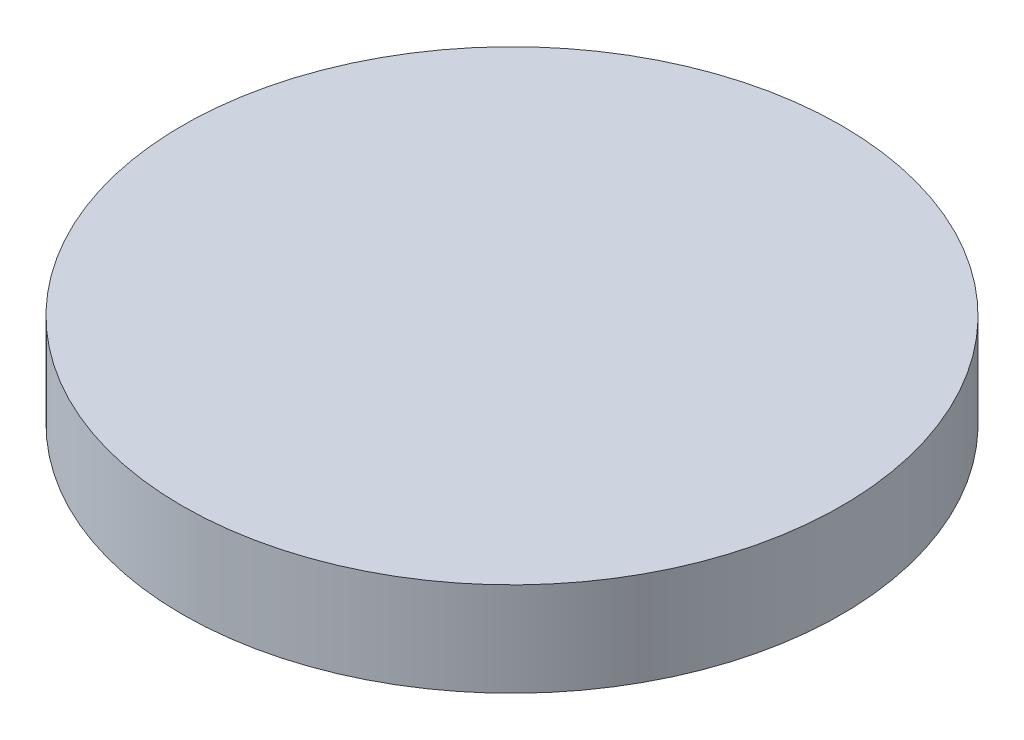
SolidWorks part; units mm, degrees
ref_plane "Front" through (0, 0, 0) normal (0, 0, 1) x (1, 0, 0)
ref_plane "Top" through (0, 0, 0) normal (0, 1, 0) x (1, 0, 0)
ref_plane "Right" through (0, 0, 0) normal (1, 0, 0) x (0, 0, -1)
sketch "Sketch1" plane through (0, 0, 0) normal (0, 1, 0) x (1, 0, 0)
  circle A0 centre (0, 0) radius 35.1042
extrude "Boss-Extrude1" add sketch "Sketch1" along normal blind 10
